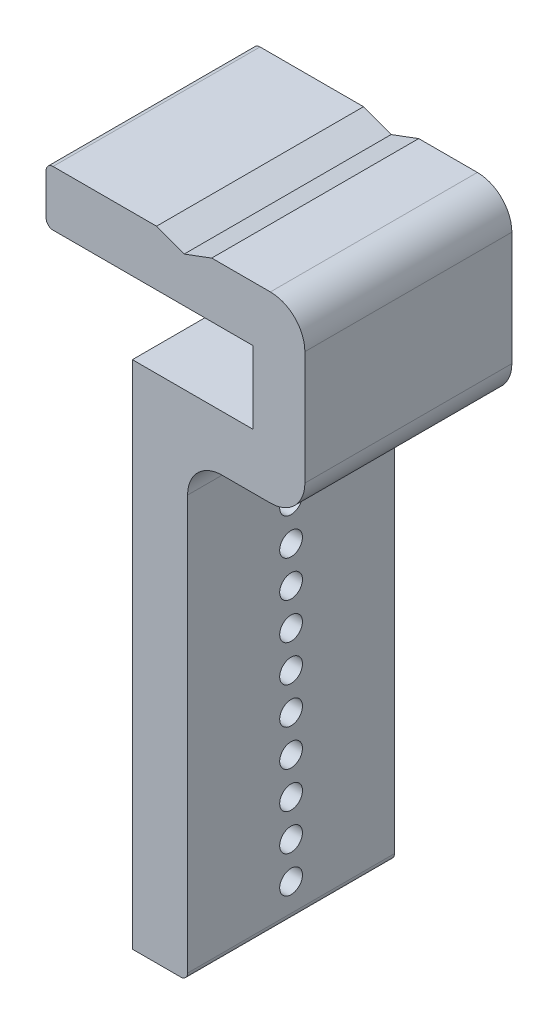
SolidWorks part; units mm, degrees
ref_plane "Front Plane" through (0, 0, 0) normal (0, 0, 1) x (1, 0, 0)
ref_plane "Top Plane" through (0, 0, 0) normal (0, 1, 0) x (1, 0, 0)
ref_plane "Right Plane" through (0, 0, 0) normal (1, 0, 0) x (0, 0, -1)
sketch "Sketch1" plane through (0, 0, 0) normal (0, 0, 1) x (1, 0, 0)
  line L0 (-14.5, 5.25) -> (-14.5, 13.25)
  line L1 (-15, 5.25) -> (15, 5.25)
  line L2 (-15, 5.25) -> (-15, -5.25)
  line L3 (-15, -5.25) -> (15, -5.25)
  line L4 (15, 5.25) -> (15, -5.25)
  line L5 (-15, 5.25) -> (15, -5.25) construction
  line L6 (-15, -5.25) -> (15, 5.25) construction
  line L7 (-14.5, 13.25) -> (23, 13.25)
  line L8 (23, 13.25) -> (23, -13.25)
  line L9 (23, -13.25) -> (6, -13.25)
  line L10 (6, -13.25) -> (6, -29.25)
  line L11 (6, -29.25) -> (-2, -29.25)
  line L12 (-2, -29.25) -> (-2, -8.5705)
  line L13 (-2, -8.5705) -> (-2, -5.25)
  line L14 (-2, -5.25) -> (15, -5.25)
  line L16 (15, 5.25) -> (15.5, 5.25)
  line L17 (15, 5.25) -> (15, -5.25)
  line L18 (15, -5.25) -> (15.5, -5.25)
  line L19 (15.5, 5.25) -> (15.5, -5.25)
  point P0 (0, 0)
  dimension "D1" = 30
  dimension "D2" = 10.5
  dimension "D3" = 8
  dimension "D4" = 8
  dimension "D5" = 29.5
  dimension "D6" = 0.5
  dimension "D7" = 8
  dimension "D8" = 25
  dimension "D9" = 8
  dimension "D10" = 16
extrude "Boss-Extrude1" add sketch "Sketch1" along normal blind 30 contours L13 L12 L11 L10 L9 L8 L7 L0 L1 L4 L3
sketch "Sketch3" plane through (0, 0, 30) normal (0, 0, 1) x (1, 0, 0)
  line L0 (1.5, 13.25) -> (9.5, 13.25)
  line L1 (-14.5, 13.25) -> (23, 13.25) construction
  line L2 (5.5, 13.25) -> (5.5, 11.75) construction
  line L3 (1.5, 13.25) -> (5.5, 11.75)
  line L4 (5.5, 11.75) -> (9.5, 13.25)
  line L5 (-14.5, 5.25) -> (-14.5, 13.25) construction
  point P5 (5.5, 13.25)
  dimension "D1" = 8
  dimension "D2" = 1.5
  dimension "D3" = 20
extrude "Cut-Extrude1" cut sketch "Sketch3" against normal blind 30
sketch "Sketch4" plane through (-14.5, 0, 0) normal (-1, 0, 0) x (0, 0, 1)
  line L2 (15, 5.25) -> (15, 2.25) construction
  line L6 (5, 5.25) -> (25, 5.25)
  line L7 (30, 5.25) -> (0, 5.25) construction
  line L8 (15, 5.25) -> (15, 2.25) construction
  line L9 (5, 5.25) -> (15, 2.25)
  line L10 (15, 2.25) -> (25, 5.25)
  line L11 (0, 5.25) -> (0, -5.25) construction
  point P5 (15, 5.25)
  point P8 (15, 5.25)
  dimension "D1" = 15
  dimension "D2" = 20
  dimension "D3" = 3
extrude "Boss-Extrude3" add sketch "Sketch4" against normal up to surface (30 mm away) up to face at (15.5, 0, 15)
sketch "Sketch5" plane through (0, -29.25, 0) normal (0, -1, 0) x (1, 0, 0)
  line L1 (-2, 30) -> (6, 30)
  line L2 (-2, 30) -> (-2, 0)
  line L3 (-2, 0) -> (6, 0)
  line L4 (6, 30) -> (6, 0)
extrude "Boss-Extrude4" add sketch "Sketch5" along normal blind 50
sketch "Sketch6" plane through (6, 0, 0) normal (1, 0, 0) x (0, 0, -1)
  line L0 (-30, -29.25) -> (0, -29.25)
  line L1 (-30, -13.25) -> (-30, -79.25) construction
  line L2 (0, -13.25) -> (0, -79.25) construction
  line L3 (0, -79.25) -> (-30, -79.25) construction
  line L4 (-15, -29.25) -> (-15, -79.25) construction
  line L5 (-15, -29.25) -> (-15, -13.25) construction
  line L6 (-30, -13.25) -> (0, -13.25) construction
  circle A0 centre (-15, -74.25) radius 1.65
  circle A1 centre (-15, -68.95) radius 1.65
  circle A2 centre (-15, -63.65) radius 1.65
  circle A3 centre (-15, -58.35) radius 1.65
  circle A4 centre (-15, -53.05) radius 1.65
  circle A5 centre (-15, -47.75) radius 1.65
  circle A6 centre (-15, -42.45) radius 1.65
  circle A7 centre (-15, -37.15) radius 1.65
  circle A8 centre (-15, -31.85) radius 1.65
  circle A9 centre (-15, -26.55) radius 1.65
  circle A10 centre (-15, -21.25) radius 1.65
  dimension "D2" = 3.3
  dimension "D3" = 5
  dimension "D4" = 3.3
  dimension "D5" = 5.3
  dimension "D6" = 3.3
  dimension "D7" = 3.3
  dimension "D8" = 3.3
  dimension "D9" = 3.3
  dimension "D10" = 5.3
  dimension "D11" = 5.3
  dimension "D12" = 5.3
  dimension "D13" = 5.3
  dimension "D14" = 3.3
  dimension "D15" = 3.3
  dimension "D16" = 3.3
  dimension "D17" = 5.3
  dimension "D18" = 5.3
  dimension "D19" = 5.3
  dimension "D20" = 3.3
  dimension "D21" = 3.3
  dimension "D22" = 5.3
  dimension "D23" = 5.3
  dimension "D1" = 50
extrude "Cut-Extrude2" cut sketch "Sketch6" against normal blind 40 contours A8 L4 | L4 A8 | L4 A7 | A7 L4 | A6 L4 | L4 A6 | A5 L4 | L4 A5 | L4 A4 | A4 L4 | A3 L4 | A2 L4 | A1 L4 | A0 L4 | L4 A0 | L4 A1 | L4 A2 | L4 A3 | A9 | A10
sketch "Sketch7" plane through (0, -79.25, 0) normal (0, -1, 0) x (1, 0, 0)
  line L0 (-2, 27.5) -> (-2, 2.5)
  line L1 (-2, 30) -> (-2, 0) construction
  line L2 (-2, 15) -> (2, 15) construction
  line L3 (-2, 27.5) -> (2, 15)
  line L4 (2, 15) -> (-2, 2.5)
  line L5 (6, 30) -> (-2, 30) construction
  point P5 (-2, 15)
  dimension "D1" = 15
  dimension "D2" = 25
  dimension "D3" = 4
extrude "Cut-Extrude3" cut sketch "Sketch7" against normal blind 65
fillet "Fillet1" radius 5 3 edges at (23, 13.25, 15) (23, -13.25, 15) (6, -13.25, 15)
fillet "Fillet3" radius 1 1 edges at (6, -79.25, 15)
fillet "Fillet4" radius 1 5 edges at (-14.5, 5.25, 27.5) (-14.5, 13.25, 15) (-14.5, 5.25, 2.5) (-14.5, 3.75, 20) (-14.5, 3.75, 10)
